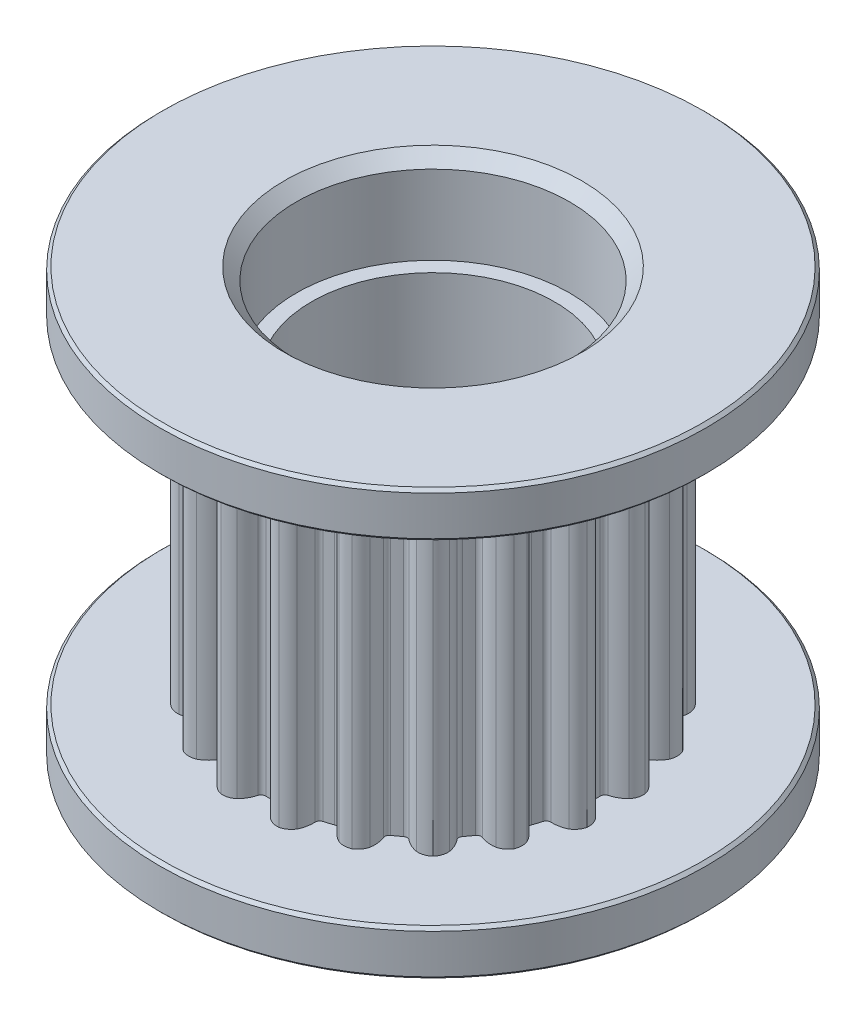
SolidWorks part; units mm, degrees
material "6061 Alloy"
ref_plane "Front Plane" through (0, 0, 0) normal (0, 0, 1) x (1, 0, 0)
ref_plane "Top Plane" through (0, 0, 0) normal (0, 1, 0) x (1, 0, 0)
ref_plane "Right Plane" through (0, 0, 0) normal (1, 0, 0) x (0, 0, -1)
sketch "BodyS" plane through (0, 0, 0) normal (0, 0, 1) x (1, 0, 0)
  line L0 (6.11, -5.5) -> (6.11, 5.5)
  line L1 (6.11, 5.5) -> (9, 5.5)
  line L2 (9, 5.5) -> (9, 7)
  line L3 (9, 7) -> (4.5, 7)
  line L4 (4.5, 7) -> (4.5, 4)
  line L5 (4.5, 4) -> (4, 4)
  line L6 (4, 4) -> (4, -4)
  line L7 (4, -4) -> (4.5, -4)
  line L8 (4.5, -4) -> (4.5, -7)
  line L9 (4.5, -7) -> (9, -7)
  line L10 (9, -7) -> (9, -5.5)
  line L11 (9, -5.5) -> (6.11, -5.5)
  line L12 (0, 0) -> (4, 0) construction
  line L13 (0, 7) -> (0, -7) construction
  dimension "BearingOD" = 9
  dimension "Height" = 14
  dimension "FlangeHeight" = 1.5
  dimension "BearingHeight" = 3
  dimension "BearingRestDiaControl" = 0.5
  dimension "RefBodyInnerDiameter" = 8
  dimension "FlangeDiaControl" = 4.5
  dimension "RefFlangeDia" = 18
  dimension "BeltPathDiaControl" = 1.61
  dimension "RefBeltPathDia" = 12.22
revolve "Body" add sketch "BodyS" angle 360 about L13
sketch "GT2ProfileS" plane through (0, 0, 0) normal (0, 1, 0) x (1, 0, 0)
  line L1 (0, -6.11) -> (0, -5.36) construction
  line L2 (-0.9955, -6.0283) -> (-0.8733, -5.2884) construction
  line L3 (0, 0) -> (-0.8733, -5.2884) construction
  line L4 (0.9955, -6.0283) -> (0, 0) construction
  arc A3 (0.2997, -5.4688) -> (0.1507, -5.3579) centre (0.1549, -5.5078) ccw
  arc A4 (-0.9955, -6.0283) -> (0.9955, -6.0283) centre (0, 0) ccw
  arc A5 (-0.2997, -5.4688) -> (-0.1507, -5.3579) centre (-0.1549, -5.5078) cw
  arc A6 (-0.2997, -5.4688) -> (-0.5497, -5.907) centre (-1.2653, -5.2085) cw
  circle A7 centre (0, 0) radius 6.11 construction
  arc A8 (-0.1507, -5.3579) -> (0.1507, -5.3579) centre (0, 0) ccw
  arc A9 (-0.5497, -5.907) -> (-0.9955, -6.0283) centre (-0.9051, -5.4808) cw
  arc A10 (0.2997, -5.4688) -> (0.5497, -5.907) centre (1.2653, -5.2085) ccw
  arc A11 (0.5497, -5.907) -> (0.9955, -6.0283) centre (0.9051, -5.4808) ccw
  circle A12 centre (0, 0) radius 5.36 construction
  dimension "BottomRadius" = 0.15
  dimension "MidRadius" = 1
  dimension "TopRadius" = 0.555
  dimension "Height" = 0.75
  dimension "XDistMidRadius" = 0.4
  dimension "ArcLengthAngle" = 18.755
  dimension "ArcLength" = 2
sketch "ThruBoreS" [suppressed] plane through (0, 0, 0) normal (0, 1, 0) x (1, 0, 0)
  circle A0 centre (0, 0) radius 4
  circle A2 centre (0, 0) radius 4 construction
extrude "ThruBore" [suppressed] cut sketch "ThruBoreS" against normal through all both and the other way through all
extrude "GT2Profile" cut sketch "GT2ProfileS" against normal up to surface and the other way up to surface up to face at (0, -5.5, 6.11) other way up to face at (0, 5.5, 9)
pattern_circular "GT2 Groove CP" count 20 over 360 about axis through (0, 0, 0) along (0, 1, 0) of "GT2Profile"
chamfer "InnerC" distance 0.4 angle 45 2 edges at (0, -7, 4.5) (0, 7, 4.5)
chamfer "OuterC" distance 0.1 angle 45 4 edges at (0, -7, 9) (0, -5.5, 9) (0, 5.5, 9) (0, 7, 9)
equation "\"NumTeeth@GT2 Groove CP\"=int(360/\"ArcLengthAngle@GT2ProfileS\")+1"
